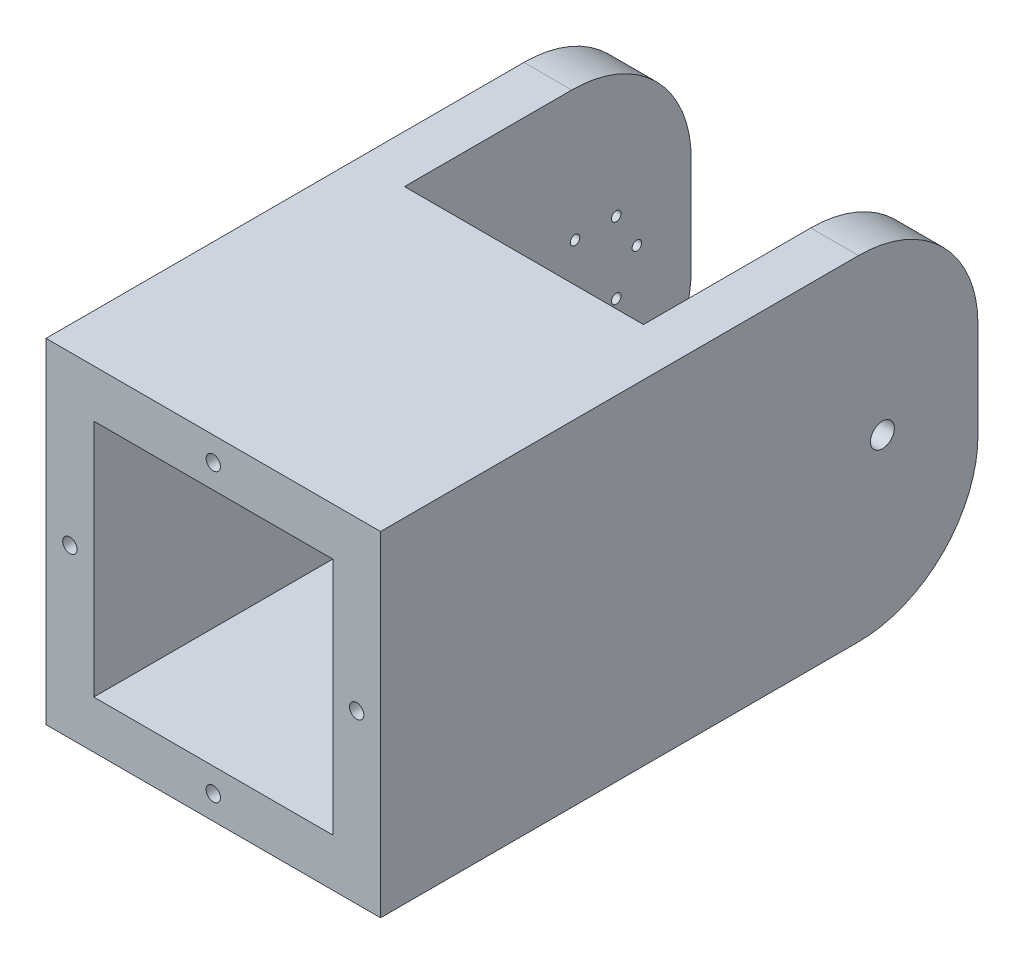
SolidWorks part; units mm, degrees
ref_plane "前视基准面" through (0, 0, 0) normal (0, 0, 1) x (1, 0, 0)
ref_plane "上视基准面" through (0, 0, 0) normal (0, 1, 0) x (1, 0, 0)
ref_plane "右视基准面" through (0, 0, 0) normal (1, 0, 0) x (0, 0, -1)
sketch "草图1" plane through (0, 0, 0) normal (0, 0, 1) x (1, 0, 0)
  line L1 (-197.2895, 106.6579) -> (-57.2895, 106.6579)
  line L2 (-197.2895, 106.6579) -> (-197.2895, -33.3421)
  line L3 (-197.2895, -33.3421) -> (-57.2895, -33.3421)
  line L4 (-57.2895, 106.6579) -> (-57.2895, -33.3421)
  line L5 (-127.2895, -33.3421) -> (-127.2895, 106.6579) construction
  line L6 (-197.2895, 36.6579) -> (-57.2895, 36.6579) construction
  line L7 (-177.2895, 86.6579) -> (-77.2895, 86.6579)
  line L8 (-177.2895, 86.6579) -> (-177.2895, -13.3421)
  line L9 (-177.2895, -13.3421) -> (-77.2895, -13.3421)
  line L10 (-77.2895, 86.6579) -> (-77.2895, -13.3421)
  line L11 (-127.2895, -13.3421) -> (-127.2895, 86.6579) construction
  line L12 (-177.2895, 36.6579) -> (-77.2895, 36.6579) construction
  point P0 (-127.2895, 36.6579)
  point P4 (-127.2895, 36.6579)
  dimension "D1" = 140
  dimension "D2" = 140
  dimension "D3" = 100
  dimension "D4" = 100
  dimension "D5" = 0
  dimension "D6" = 20
extrude "凸台-拉伸3" add sketch "草图1" along normal blind 250
sketch "草图2" plane through (0, 0, 0) normal (0, 0, -1) x (-1, 0, 0)
  line L0 (197.2895, -33.3421) -> (57.2895, -33.3421) construction
  line L1 (77.2895, 106.6579) -> (177.2895, 106.6579)
  line L2 (77.2895, 106.6579) -> (77.2895, -33.3421)
  line L3 (77.2895, -33.3421) -> (177.2895, -33.3421)
  line L4 (177.2895, 106.6579) -> (177.2895, -33.3421)
  line L5 (127.2895, -33.3421) -> (127.2895, 106.6579) construction
  line L6 (77.2895, 36.6579) -> (177.2895, 36.6579) construction
  line L7 (57.2895, 106.6579) -> (197.2895, 106.6579) construction
  line L8 (177.2895, 86.6579) -> (177.2895, -13.3421) construction
  line L9 (77.2895, -13.3421) -> (77.2895, 86.6579) construction
  point P0 (127.2895, 36.6579)
  dimension "D1" = 0
  dimension "D2" = 0
  dimension "D3" = 0
  dimension "D4" = 0
extrude "切除-拉伸1" cut sketch "草图2" against normal blind 120
sketch "草图4" plane through (0, 0, 250) normal (0, 0, 1) x (1, 0, 0)
  line L0 (-77.2895, 86.6579) -> (-177.2895, 86.6579) construction
  line L2 (-77.2895, -13.3421) -> (-77.2895, 86.6579) construction
  line L3 (-197.2895, -33.3421) -> (-57.2895, -33.3421) construction
  circle A0 centre (-127.2895, 36.6579) radius 15.7044
  circle A1 centre (-187.2895, 36.6579) radius 3
  circle A2 centre (-127.2895, 96.6579) radius 3
  circle A3 centre (-67.2895, 36.6579) radius 3
  circle A4 centre (-127.2895, -23.3421) radius 3
  point P19 (-127.2895, 36.6579)
  dimension "D3" = 60
  dimension "D1" = 50
  dimension "D2" = 50
  dimension "D4" = 70
  dimension "D5" = 4
extrude "切除-拉伸2" cut sketch "草图4" against normal blind 10
sketch "草图8" plane through (-197.2895, 0, 0) normal (-1, 0, 0) x (0, 0, 1)
  line L0 (0, 106.6579) -> (0, -33.3421) construction
  line L1 (250, 106.6579) -> (0, 106.6579) construction
  circle A0 centre (40, 36.6579) radius 30
  circle A1 centre (40, 36.6579) radius 17.25
  circle A2 centre (22.75, 36.6579) radius 2
  circle A3 centre (31.375, 51.5968) radius 2
  circle A4 centre (48.625, 51.5968) radius 2
  circle A5 centre (57.25, 36.6579) radius 2
  circle A6 centre (48.625, 21.719) radius 2
  circle A7 centre (31.375, 21.719) radius 2
  point P21 (40, 36.6579)
  dimension "D1" = 40
  dimension "D3" = 34.5
  dimension "D4" = 6
  dimension "D2" = 70
extrude "切除-拉伸3" cut sketch "草图8" against normal blind 20 contours A2 | A7 | A6 | A5 | A4 | A3
sketch "草图9" plane through (-57.2895, 0, 0) normal (1, 0, 0) x (0, 0, -1)
  line L0 (0, -33.3421) -> (0, 106.6579) construction
  line L2 (-250, -33.3421) -> (0, -33.3421) construction
  circle A0 centre (-40, 36.6579) radius 22.5
  circle A1 centre (-40, 36.6579) radius 5
  dimension "D1" = 40
  dimension "D2" = 70
fillet "圆角1" radius 50 4 edges at (-67.2895, 106.6579, 0) (-187.2895, 106.6579, 0) (-187.2895, -33.3421, 0) (-67.2895, -33.3421, 0)
sketch "草图10" plane through (-77.2895, 0, 0) normal (-1, 0, 0) x (0, 0, 1)
  circle A0 centre (40, 36.6579) radius 22.5
  circle A1 centre (40, 36.6579) radius 22.5 construction
  dimension "D1" = 0
extrude "切除-拉伸4" cut sketch "草图10" against normal blind 10 contours A0
sketch "草图11" plane through (-67.2895, 0, 0) normal (-1, 0, 0) x (0, 0, 1)
  circle A0 centre (40, 36.6579) radius 5
extrude "切除-拉伸10" cut sketch "草图11" against normal blind 12
